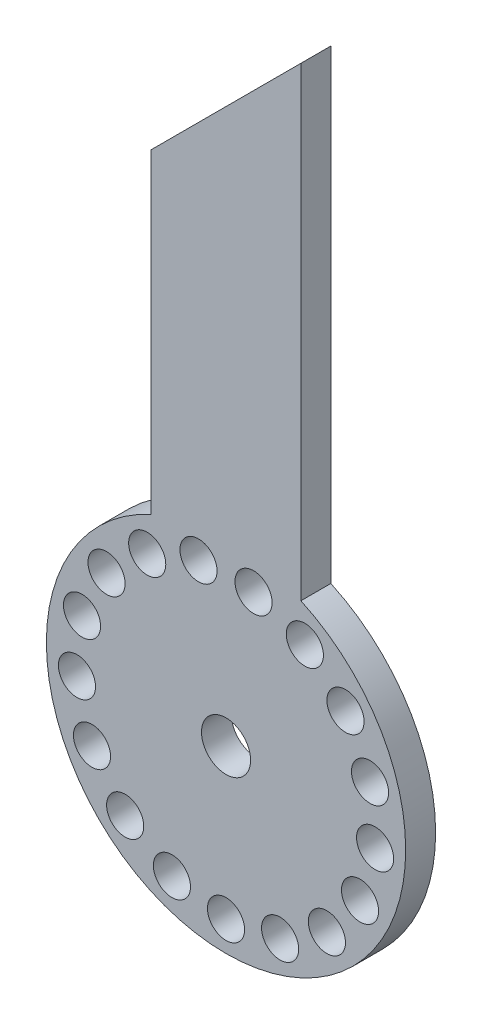
SolidWorks part; units mm, degrees
ref_plane "前视基准面" through (0, 0, 0) normal (0, 0, 1) x (1, 0, 0)
ref_plane "上视基准面" through (0, 0, 0) normal (0, 1, 0) x (1, 0, 0)
ref_plane "右视基准面" through (0, 0, 0) normal (1, 0, 0) x (0, 0, -1)
sketch "草图8" plane through (0, 0, 0) normal (0, 0, 1) x (1, 0, 0)
  line L1 (-12.5, 150) -> (12.5, 150)
  line L2 (-12.5, 150) -> (-12.5, 27.2718)
  line L4 (12.5, 150) -> (12.5, 27.2718)
  arc A0 (-12.5, 27.2718) -> (12.5, 27.2718) centre (0, 0) ccw
  dimension "D1" = 25
  dimension "D2" = 60
extrude "凸台-拉伸3" add sketch "草图8" along normal blind 5
ref_plane "基准面1" through (0, 0, 5) normal (0, 0, 1) x (1, 0, 0)
sketch "草图12" plane through (0, 0, 5) normal (0, 0, 1) x (1, 0, 0)
  line L0 (12.5, 27.2718) -> (12.5, 150) construction
  line L1 (-12.5, 150) -> (12.5, 150)
  line L2 (-12.5, 150) -> (-12.5, 125)
  line L3 (-12.5, 125) -> (12.5, 125)
  line L4 (12.5, 150) -> (12.5, 125)
  dimension "D1" = 25
extrude "切除-拉伸2" cut sketch "草图12" against normal blind 5
sketch "草图13" plane through (0, 0, 5) normal (0, 0, 1) x (1, 0, 0)
  line L1 (-12.5, 125) -> (12.5, 125)
  line L2 (-12.5, 125) -> (-12.5, 100)
  line L5 (-12.5, 100) -> (12.5, 125)
  dimension "D1" = 25
extrude "切除-拉伸3" cut sketch "草图13" against normal blind 5
sketch "草图14" plane through (0, 0, 5) normal (0, 0, 1) x (1, 0, 0)
  circle A0 centre (0, 0) radius 4.1
extrude "切除-拉伸4" cut sketch "草图14" against normal blind 5
sketch "草图16" plane through (0, 0, 5) normal (0, 0, 1) x (1, 0, 0)
  circle A0 centre (0, -25) radius 3.1
  circle A1 centre (0, 0) radius 4.1 construction
  circle A2 centre (-9.031, -23.3118) radius 3.1
  circle A3 centre (-16.8424, -18.4752) radius 3.1
  circle A4 centre (-22.3791, -11.1435) radius 3.1
  circle A5 centre (-24.8934, -2.3067) radius 3.1
  circle A6 centre (-24.0456, 6.8416) radius 3.1
  circle A7 centre (-19.9504, 15.0659) radius 3.1
  circle A8 centre (-13.1608, 21.2554) radius 3.1
  circle A9 centre (-4.5937, 24.5743) radius 3.1
  circle A10 centre (4.5937, 24.5743) radius 3.1
  circle A11 centre (13.1608, 21.2554) radius 3.1
  circle A12 centre (19.9504, 15.0659) radius 3.1
  circle A13 centre (24.0456, 6.8416) radius 3.1
  circle A14 centre (24.8934, -2.3067) radius 3.1
  circle A15 centre (22.3791, -11.1435) radius 3.1
  circle A16 centre (16.8424, -18.4752) radius 3.1
  circle A17 centre (9.031, -23.3118) radius 3.1
  point P38 (0, 0)
  dimension "D1" = 25
  dimension "D3" = 6.2
  dimension "D2" = 17
extrude "切除-拉伸5" cut sketch "草图16" against normal blind 5
sketch "草图17" plane through (0, 0, 5) normal (0, 0, 1) x (1, 0, 0)
  line L0 (-12.5, 100) -> (12.5, 125)
  line L1 (-12.5, 100) -> (-12.5, 70)
  line L2 (12.5, 125) -> (12.5, 95)
  line L3 (-12.5, 70) -> (12.5, 95)
  line L4 (12.5, 27.2718) -> (12.5, 125) construction
  dimension "D1" = 30
extrude "切除-拉伸6" cut sketch "草图17" against normal blind 5
sketch "草图18" plane through (0, 0, 5) normal (0, 0, 1) x (1, 0, 0)
  line L1 (-12.5, 70) -> (12.5, 70)
  line L2 (-12.5, 70) -> (-12.5, 105)
  line L3 (-12.5, 105) -> (12.5, 105)
  line L4 (12.5, 70) -> (12.5, 105)
  dimension "D1" = 35
  dimension "D2" = 25
extrude "凸台-拉伸4" add sketch "草图18" against normal blind 5
sketch "草图19" plane through (0, 0, 5) normal (0, 0, 1) x (1, 0, 0)
  line L1 (-12.5, 105) -> (12.5, 105)
  line L2 (-12.5, 105) -> (-12.5, 80)
  line L5 (-12.5, 80) -> (12.5, 105)
  dimension "D1" = 25
extrude "切除-拉伸7" cut sketch "草图19" against normal blind 5
